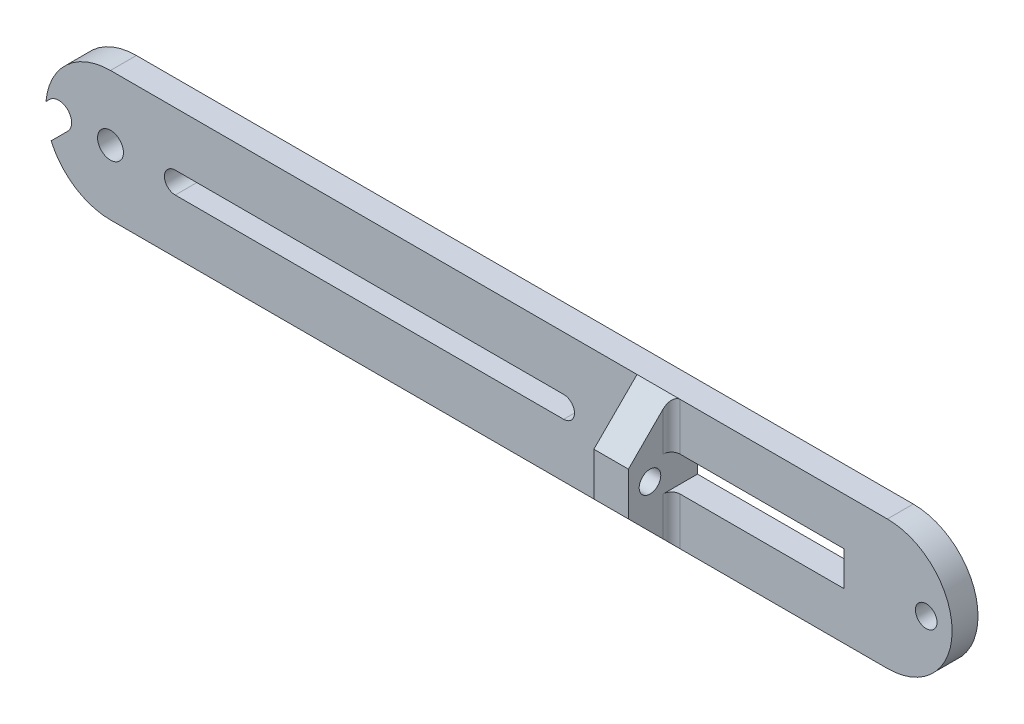
SolidWorks part; units mm, degrees
ref_plane "Plan de face" through (0, 0, 0) normal (0, 0, 1) x (1, 0, 0)
ref_plane "Plan de dessus" through (0, 0, 0) normal (0, 1, 0) x (1, 0, 0)
ref_plane "Plan de droite" through (0, 0, 0) normal (1, 0, 0) x (0, 0, -1)
sketch "Esquisse1" plane through (0, 0, 0) normal (0, 0, 1) x (1, 0, 0)
  line L0 (-74.3787, 0) -> (69.7437, 0) construction
  line L1 (0, 0) -> (0, 19.0596) construction
  line L2 (90, -15) -> (-90, -15)
  line L3 (90, 15) -> (-90, 15)
  line L4 (15, -2.5) -> (-75, -2.5)
  line L5 (40, -4) -> (80, -4)
  line L6 (40, -4) -> (40, 4)
  line L7 (40, 4) -> (80, 4)
  line L8 (80, -4) -> (80, 4)
  line L9 (40, -4) -> (80, 4) construction
  line L10 (40, 4) -> (80, -4) construction
  line L11 (-75, 2.5) -> (15, 2.5)
  arc A0 (90, -15) -> (90, 15) centre (90, 0) ccw
  circle A1 centre (99, 0) radius 2.5
  circle A2 centre (-90, 0) radius 3
  arc A3 (-90, -15) -> (-90, 15) centre (-90, 0) cw
  arc A5 (-75, 2.5) -> (-75, -2.5) centre (-75, 0) ccw
  arc A6 (15, -2.5) -> (15, 2.5) centre (15, 0) ccw
  point P4 (60, 0)
  point P17 (0, -15)
  point P20 (0, 15)
  dimension "D1" = 30
  dimension "D2" = 9
  dimension "D4" = 8
  dimension "D5" = 40
  dimension "D6" = 60
extrude "Boss.-Extru.1" add sketch "Esquisse1" along normal blind 6
sketch "Esquisse2" plane through (40, 0, 0) normal (1, 0, 0) x (0, 0, -1)
  line L0 (0, -4) -> (-6, 4) construction
  line L1 (-6, 4) -> (-6, 0) construction
  line L2 (-6, 4) -> (-6, -4) construction
  line L3 (-6, 0) -> (-15.5036, 0) construction
  line L4 (-6, 15) -> (-6, -15) construction
  line L6 (-16, 5) -> (-16, -5)
  line L8 (-6, 5) -> (-6, -5)
  line L9 (-16, 5) -> (-6, -5) construction
  line L10 (-16, -5) -> (-6, 5) construction
  line L11 (-6, -15) -> (-16, -5)
  line L12 (-6, -15) -> (-6, -5)
  line L13 (-6, 5) -> (-6, 15)
  line L14 (-6, 15) -> (-16, 5)
  circle A0 centre (-11, 0) radius 2.5
  point P7 (-11, 0)
  dimension "D3" = 5
  dimension "D1" = 10
  dimension "D2" = 10
extrude "Boss.-Extru.2" add sketch "Esquisse2" against normal blind 8
fillet "Congé2" radius 2 2 edges
sketch "Esquisse3" plane through (32, 0, 0) normal (-1, 0, 0) x (0, 0, 1)
  line L0 (11, 0) -> (11, 4) construction
  line L1 (11, 0) -> (14.4641, 2) construction
  line L2 (11, 0) -> (14.4641, -2) construction
  line L3 (11, 4) -> (14.4641, 2)
  line L4 (14.4641, 2) -> (14.4641, -2)
  line L5 (14.4641, -2) -> (11, -4)
  line L6 (7.5359, 2) -> (7.5359, -2)
  line L7 (11, 4) -> (7.5359, 2)
  line L8 (7.5359, -2) -> (11, -4)
  dimension "D2" = 60
  dimension "D3" = 60
extrude "Enlèv. mat.-Extru.1" cut sketch "Esquisse3" against normal blind 4
sketch "Esquisse4" plane through (0, 0, 6) normal (0, 0, 1) x (1, 0, 0)
  line L0 (-90, 0) -> (-105, 0) construction
  line L1 (-105, 0) -> (-102, 0) construction
  line L2 (-102, 0) -> (-99.8787, -2.1213) construction
  line L3 (-99.8787, -2.1213) -> (-104.1213, 2.1213)
  line L4 (-99.8787, -2.1213) -> (-104.1213, 2.1213)
  line L5 (-99.8787, -2.1213) -> (-104.2614, -6.504)
  line L6 (-104.1213, 2.1213) -> (-108.504, -2.2614)
  line L7 (-104.2614, -6.504) -> (-108.504, -2.2614)
  arc A0 (-90, 15) -> (-90, -15) centre (-90, 0) ccw construction
  circle A1 centre (-102, 0) radius 3
  arc M9 (-90, 15) -> (-90, -15) centre (-90, 0) ccw
  dimension "D1" = 3
  dimension "D2" = 135
extrude "Enlèv. mat.-Extru.4" cut sketch "Esquisse4" against normal blind 10 contours L3 A1 | A1 L6 M9 | A1 L5 M9 | L3 A1
